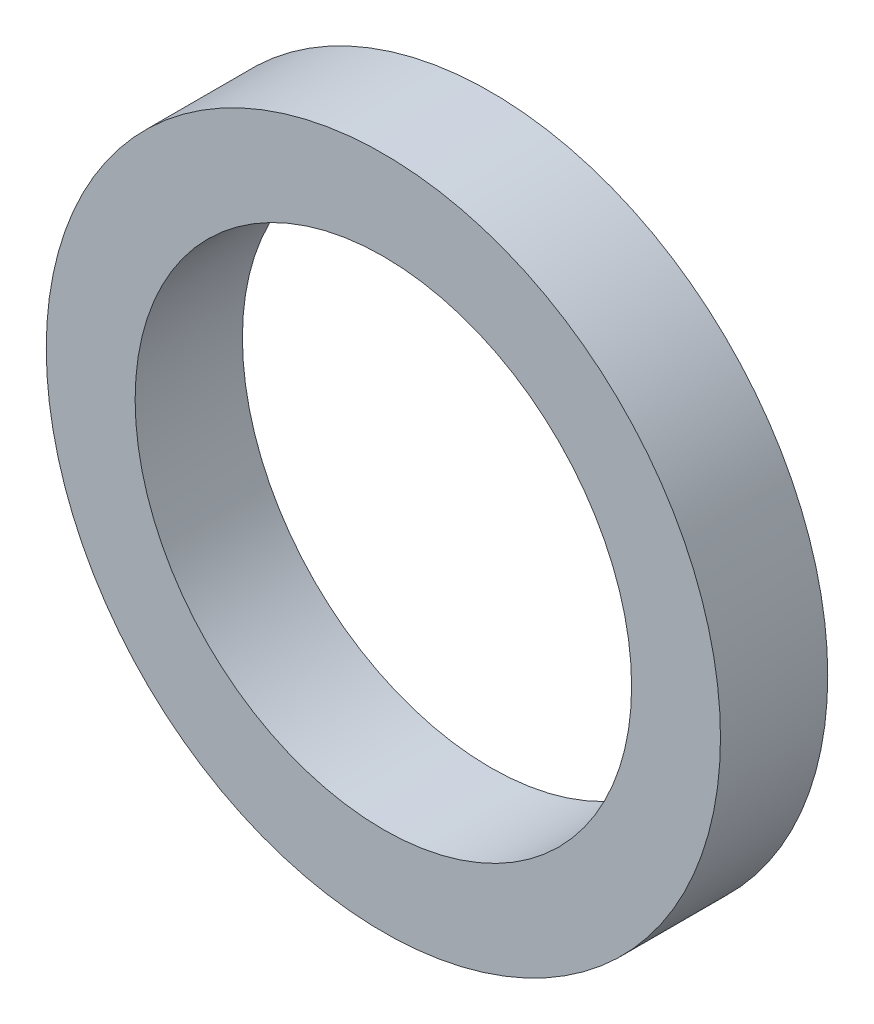
SolidWorks part; units mm, degrees
material "PET"
ref_plane "Front" through (0, 0, 0) normal (0, 0, 1) x (1, 0, 0)
ref_plane "Top" through (0, 0, 0) normal (0, 1, 0) x (1, 0, 0)
ref_plane "Right" through (0, 0, 0) normal (1, 0, 0) x (0, 0, -1)
ref_plane "Plane1" through (0, 0, 0) normal (0, -1, 0) x (1, 0, 0)
sketch "Sketch1" plane through (0, 0, 0) normal (0, -1, 0) x (1, 0, 0)
  line L0 (8.1, 3.5) -> (8.1, 0)
  line L1 (8.1, 0) -> (11, 0)
  line L2 (11, 0) -> (11, 3.5)
  line L3 (11, 3.5) -> (8.1, 3.5)
  line L4 (0, 3.5) -> (0, 0) construction
revolve "Revolve1" add sketch "Sketch1" angle 360 about L4
